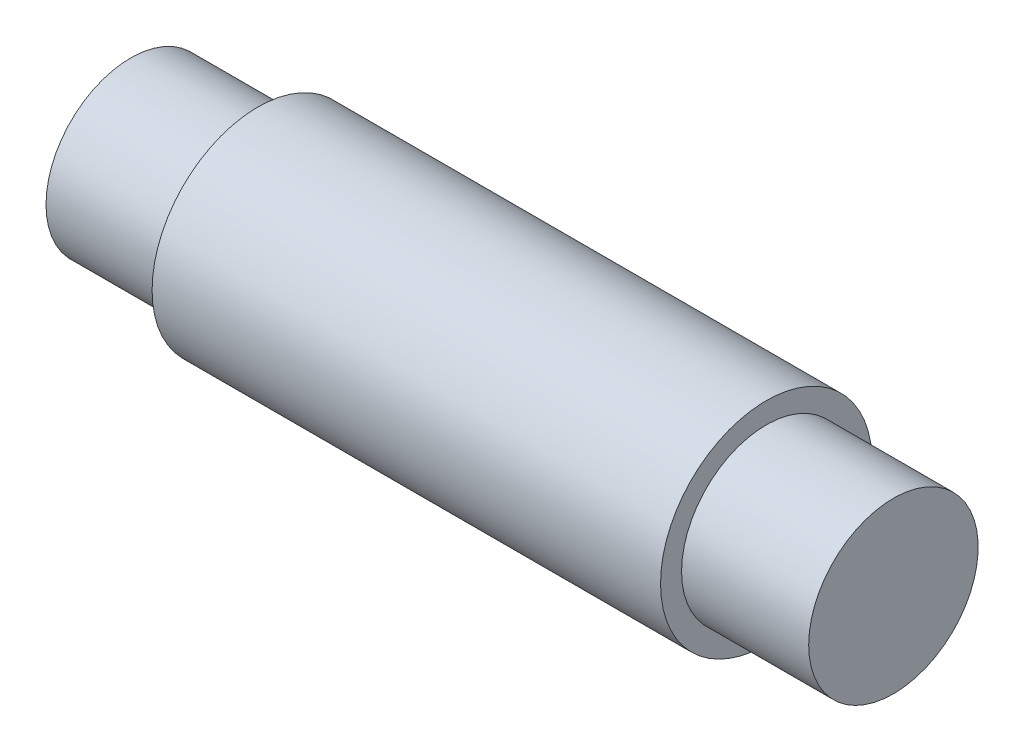
SolidWorks part; units mm, degrees
ref_plane "Front Plane" through (0, 0, 0) normal (0, 0, 1) x (1, 0, 0)
ref_plane "Top Plane" through (0, 0, 0) normal (0, 1, 0) x (1, 0, 0)
ref_plane "Right Plane" through (0, 0, 0) normal (1, 0, 0) x (0, 0, -1)
sketch "Sketch1" plane through (0, 0, 0) normal (0, 0, 1) x (1, 0, 0)
  line L8 (0, 0) -> (28.575, 0)
  line L9 (28.575, 0) -> (28.575, 3.175)
  line L10 (28.575, 3.175) -> (23.8125, 3.175)
  line L11 (23.8125, 3.175) -> (23.8125, 3.9624)
  line L12 (23.8125, 3.9624) -> (4.7625, 3.9624)
  line L13 (4.7625, 3.9624) -> (4.7625, 3.175)
  line L14 (4.7625, 3.175) -> (0, 3.175)
  line L15 (0, 3.175) -> (0, 0)
  point P8 (0, 0)
  point P10 (0, 3.175)
  point P11 (0, 0)
  dimension "D1" = 28.575
  dimension "D2" = 19.05
  dimension "D3" = 3.9624
  dimension "D4" = 3.175
revolve "Revolve1" add sketch "Sketch1" angle 360 about L8
